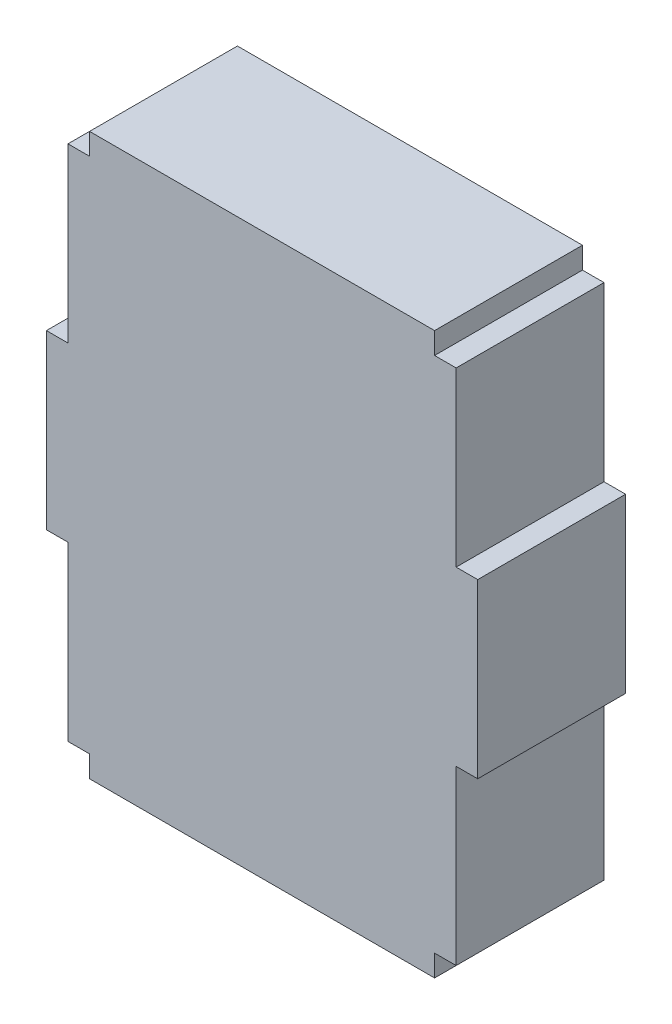
SolidWorks part; units mm, degrees
material "PBTP"
ref_plane "Front Plane" through (0, 0, 0) normal (0, 0, 1) x (1, 0, 0)
ref_plane "Top Plane" through (0, 0, 0) normal (0, 1, 0) x (1, 0, 0)
ref_plane "Right Plane" through (0, 0, 0) normal (1, 0, 0) x (0, 0, -1)
sketch "Sketch1" plane through (0, 0, 0) normal (0, 0, 1) x (1, 0, 0)
  line L0 (0, 0) -> (0, 11.375)
  line L1 (-3.5, 0) -> (3.5, 0)
  line L2 (3.5, 0) -> (3.5, 0.4375)
  line L3 (3.5, 0.4375) -> (3.9375, 0.4375)
  line L4 (3.9375, 0.4375) -> (3.9375, 3.9375)
  line L5 (3.9375, 3.9375) -> (4.375, 3.9375)
  line L6 (4.375, 3.9375) -> (4.375, 7.4375)
  line L7 (4.375, 7.4375) -> (3.9375, 7.4375)
  line L8 (3.9375, 7.4375) -> (3.9375, 10.9375)
  line L9 (3.5, 10.9375) -> (3.9375, 10.9375)
  line L10 (3.5, 10.9375) -> (3.5, 11.375)
  line L11 (3.5, 11.375) -> (-3.5, 11.375)
  line L12 (-3.5, 0) -> (-3.5, 0.4375)
  line L13 (-3.5, 0.4375) -> (-3.9375, 0.4375)
  line L14 (-3.9375, 0.4375) -> (-3.9375, 3.9375)
  line L15 (-3.9375, 3.9375) -> (-4.375, 3.9375)
  line L16 (-4.375, 3.9375) -> (-4.375, 7.4375)
  line L17 (-4.375, 7.4375) -> (-3.9375, 7.4375)
  line L18 (-3.9375, 7.4375) -> (-3.9375, 10.9375)
  line L19 (-3.5, 10.9375) -> (-3.9375, 10.9375)
  line L20 (-3.5, 10.9375) -> (-3.5, 11.375)
  dimension "D1" = 7
extrude "Boss-Extrude1" add sketch "Sketch1" along normal blind 3 contours L6 L7 L8 L9 L10 L11 L20 L19 L18 L17 L16 L15 L14 L13 L12 L1 L2 L3 L4 L5
